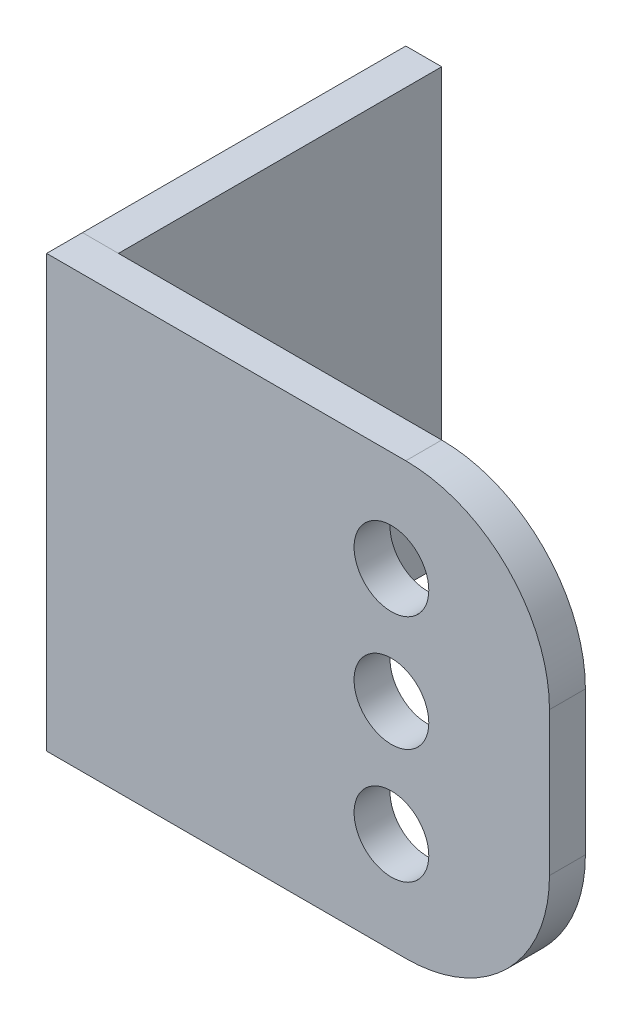
SolidWorks part; units mm, degrees
material "AISI 4130 Steel, annealed at 865C"
ref_plane "Front Plane" through (0, 0, 0) normal (0, 0, 1) x (1, 0, 0)
ref_plane "Top Plane" through (0, 0, 0) normal (0, 1, 0) x (1, 0, 0)
ref_plane "Right Plane" through (0, 0, 0) normal (1, 0, 0) x (0, 0, -1)
sketch "Sketch1" plane through (0, 0, 0) normal (0, 0, 1) x (1, 0, 0)
  line L0 (0, -374.8954) -> (0, 18369.8741) construction
  line L6 (0, 19.05) -> (44.45, 19.05)
  line L7 (0, 19.05) -> (0, -19.05)
  line L8 (0, -19.05) -> (44.45, -19.05)
  line L9 (44.45, 19.05) -> (44.45, -19.05)
  line L10 (22.225, -19.05) -> (22.225, 19.05) construction
  line L11 (0, 0) -> (44.45, 0) construction
  point P291 (22.225, 0)
  dimension "D1" = 44.45
  dimension "D2" = 38.1
extrude "Boss-Extrude1" add sketch "Sketch1" along normal blind 3.175
sketch "Sketch2" plane through (0, 0, 3.175) normal (0, 0, 1) x (1, 0, 0)
  line L0 (30.48, 10.16) -> (30.48, -10.16) construction
  line L1 (0, 0) -> (44.45, 0) construction
  line L2 (0, 19.05) -> (0, -19.05) construction
  line L3 (44.45, -19.05) -> (44.45, 19.05) construction
  circle A0 centre (30.48, 10.16) radius 3.302
  circle A1 centre (30.48, -10.16) radius 3.302
  circle A2 centre (30.48, 0) radius 3.302
  point P4 (30.48, 0)
  dimension "D1" = 6.604
  dimension "D2" = 30.48
  dimension "D3" = 10.16
extrude "Cut-Extrude1" cut sketch "Sketch2" against normal through all both and the other way through all
sketch "Sketch3" plane through (0, 0, 0) normal (0, 0, -1) x (-1, 0, 0)
  line L0 (0, -19.05) -> (-44.45, -19.05) construction
  line L1 (0, 19.05) -> (-3.175, 19.05)
  line L2 (0, 19.05) -> (0, -19.05)
  line L3 (0, -19.05) -> (-3.175, -19.05)
  line L4 (-3.175, 19.05) -> (-3.175, -19.05)
  line L5 (-1.5875, -19.05) -> (-1.5875, 19.05) construction
  line L6 (0, 0) -> (-3.175, 0) construction
  point P148 (-1.5875, 0)
  dimension "D1" = 3.175
extrude "Boss-Extrude2" add sketch "Sketch3" along normal blind 28.575 separate body
fillet "Fillet1" radius 12.7 2 edges at (44.45, -19.05, 1.5875) (44.45, 19.05, 1.5875)
